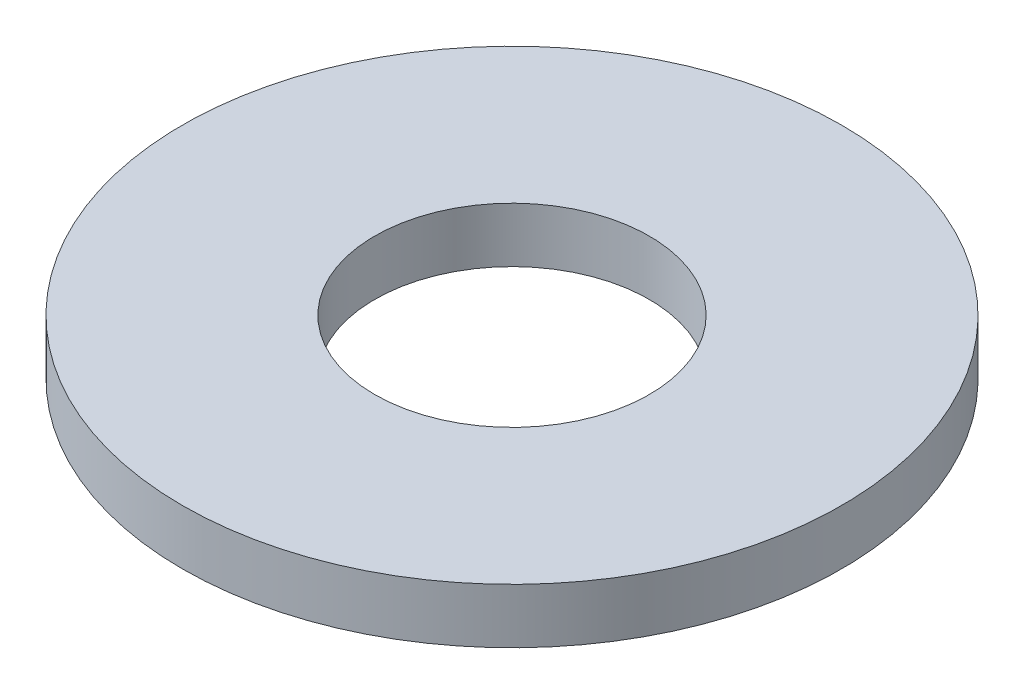
SolidWorks part; units mm, degrees
ref_plane "前视基准面" through (0, 0, 0) normal (0, 0, 1) x (1, 0, 0)
ref_plane "上视基准面" through (0, 0, 0) normal (0, 1, 0) x (1, 0, 0)
ref_plane "右视基准面" through (0, 0, 0) normal (1, 0, 0) x (0, 0, -1)
sketch "草图1" plane through (0, 0, 0) normal (0, 1, 0) x (1, 0, 0)
  circle A0 centre (0, 0) radius 2.5
  circle A1 centre (0, 0) radius 6
extrude "凸台-拉伸1" add sketch "草图1" along normal blind 1
